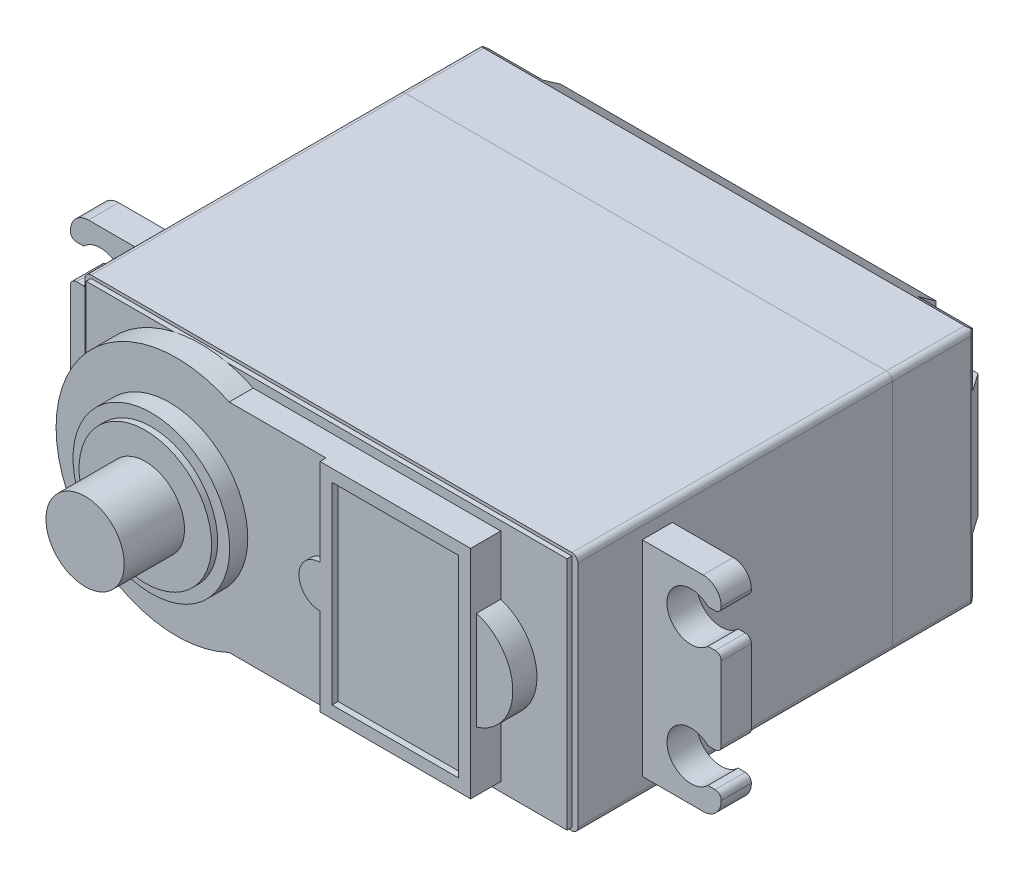
SolidWorks part; units mm, degrees
ref_plane "Front Plane" through (0, 0, 0) normal (0, 0, 1) x (1, 0, 0)
ref_plane "Top Plane" through (0, 0, 0) normal (0, 1, 0) x (1, 0, 0)
ref_plane "Right Plane" through (0, 0, 0) normal (1, 0, 0) x (0, 0, -1)
sketch "Sketch1" plane through (0, 0, 0) normal (0, 0, 1) x (1, 0, 0)
  line L1 (-20.45, 10) -> (20.45, 10)
  line L2 (-20.45, 10) -> (-20.45, -10)
  line L3 (-20.45, -10) -> (20.45, -10)
  line L4 (20.45, 10) -> (20.45, -10)
  line L5 (-20.45, 10) -> (20.45, -10) construction
  line L6 (-20.45, -10) -> (20.45, 10) construction
  point P0 (0, 0)
  dimension "D1" = 40.9
  dimension "D2" = 20
extrude "Boss-Extrude1" add sketch "Sketch1" along normal blind 19.3
sketch "Sketch2" plane through (0, 0, 19.3) normal (0, 0, 1) x (1, 0, 0)
  line L4 (20.45, -10) -> (20.45, 10)
  line L5 (20.45, 10) -> (-20.45, 10)
  line L6 (-20.45, 10) -> (-20.45, -10)
  line L7 (-20.45, -10) -> (20.45, -10)
  line L8 (20.45, -10) -> (20.45, 10)
  line L9 (20.45, 10) -> (-20.45, 10)
  line L10 (-20.45, 10) -> (-20.45, -10)
  line L11 (-20.45, -10) -> (20.45, -10)
  dimension "D1" = 0
extrude "Boss-Extrude2" add sketch "Sketch2" along normal blind 6.8 separate body
sketch "Sketch3" plane through (0, 0, 0) normal (0, 0, -1) x (-1, 0, 0)
  line L4 (-20.45, 10) -> (-20.45, -10)
  line L5 (-20.45, -10) -> (20.45, -10)
  line L6 (20.45, -10) -> (20.45, 10)
  line L7 (20.45, 10) -> (-20.45, 10)
  line L8 (-20.45, 10) -> (-20.45, -10)
  line L9 (-20.45, -10) -> (20.45, -10)
  line L10 (20.45, -10) -> (20.45, 10)
  line L11 (20.45, 10) -> (-20.45, 10)
  dimension "D1" = 0
extrude "Boss-Extrude3" add sketch "Sketch3" along normal blind 8.5 separate body
chamfer "Chamfer1" distance 2 angle 35 4 edges at (-20.45, 0, -8.5) (0, -10, -8.5) (20.45, 0, -8.5) (0, 10, -8.5)
sketch "Sketch4" plane through (0, 0, -8.5) normal (0, 0, -1) x (-1, 0, 0)
  line L0 (0, 8.5996) -> (0, -8.5996) construction
  line L1 (-20.45, 10) -> (-15.57, 10)
  line L2 (-20.45, 10) -> (-20.45, 5.12)
  line L3 (-20.45, 5.12) -> (-17.57, 5.12)
  line L4 (-15.57, 10) -> (-15.57, 7.12)
  line L5 (19.0496, 8.5996) -> (-19.0496, 8.5996) construction
  line L6 (-19.0496, -8.5996) -> (19.0496, -8.5996) construction
  line L7 (0, 0) -> (19.0496, 0) construction
  line L8 (19.0496, -8.5996) -> (19.0496, 8.5996) construction
  line L9 (20.45, 5.12) -> (17.57, 5.12)
  line L10 (20.45, 10) -> (20.45, 5.12)
  line L11 (20.45, 10) -> (15.57, 10)
  line L12 (15.57, 10) -> (15.57, 7.12)
  line L13 (15.57, -10) -> (15.57, -7.12)
  line L14 (20.45, -10) -> (15.57, -10)
  line L15 (20.45, -10) -> (20.45, -5.12)
  line L16 (20.45, -5.12) -> (17.57, -5.12)
  line L17 (-15.57, -10) -> (-15.57, -7.12)
  line L18 (-20.45, -5.12) -> (-17.57, -5.12)
  line L19 (-20.45, -10) -> (-20.45, -5.12)
  line L20 (-20.45, -10) -> (-15.57, -10)
  arc A0 (-17.57, 5.12) -> (-15.57, 7.12) centre (-17.57, 7.12) ccw
  arc A1 (17.57, 5.12) -> (15.57, 7.12) centre (17.57, 7.12) cw
  arc A2 (17.57, -5.12) -> (15.57, -7.12) centre (17.57, -7.12) ccw
  arc A3 (-17.57, -5.12) -> (-15.57, -7.12) centre (-17.57, -7.12) cw
  dimension "D3" = 2
  dimension "D1" = 4.88
  dimension "D2" = 4.88
extrude "Cut-Extrude1" cut sketch "Sketch4" against normal blind 1.5
sketch "Sketch5" plane through (0, 0, 26.1) normal (0, 0, 1) x (1, 0, 0)
  line L0 (20.45, 10) -> (-20.45, 10) construction
  line L1 (-19.95, 9.75) -> (19.95, 9.75)
  line L2 (-19.95, 9.75) -> (-19.95, -9.75)
  line L3 (-19.95, -9.75) -> (19.95, -9.75)
  line L4 (19.95, 9.75) -> (19.95, -9.75)
  line L5 (-19.95, 9.75) -> (19.95, -9.75) construction
  line L6 (-19.95, -9.75) -> (19.95, 9.75) construction
  line L7 (-20.45, 10) -> (-20.45, -10) construction
  point P0 (0, 0)
  dimension "D1" = 0.25
  dimension "D2" = 0.5
extrude "Boss-Extrude4" add sketch "Sketch5" along normal blind 0.4
sketch "Sketch6" plane through (0, 0, 26.5) normal (0, 0, 1) x (1, 0, 0)
  line L0 (-19.95, 0) -> (19.95, 0) construction
  line L1 (-19.95, 9.75) -> (-19.95, -9.75) construction
  line L2 (19.95, -9.75) -> (19.95, 9.75) construction
  line L3 (-20.45, 10) -> (-20.45, -10) construction
  line L4 (20.45, 10) -> (-20.45, 10) construction
  line L5 (-6.09, 10) -> (-6.09, -10) construction
  line L6 (-20.45, -10) -> (20.45, -10) construction
  line L7 (-6.09, 8.9995) -> (14.45, 8.9995)
  line L8 (14.45, 8.9995) -> (14.45, 4.0952)
  line L9 (20.45, -10) -> (20.45, 10) construction
  line L10 (14.45, -8.9995) -> (14.45, -4.0952)
  line L11 (-6.09, -8.9995) -> (14.45, -8.9995)
  arc A0 (-6.09, 8.9995) -> (-6.09, -8.9995) centre (-10.45, 0) ccw
  arc A1 (14.45, -4.0952) -> (14.45, 4.0952) centre (13.1549, 0) ccw
  point P24 (17.45, 0)
  dimension "D1" = 14.36
  dimension "D2" = 3
  dimension "D3" = 6
extrude "Boss-Extrude5" add sketch "Sketch6" along normal blind 2
sketch "Sketch7" plane through (0, 0, 28.5) normal (0, 0, 1) x (1, 0, 0)
  circle A0 centre (-11.0436, 0) radius 6.5
  dimension "D1" = 13
extrude "Boss-Extrude6" add sketch "Sketch7" along normal blind 1.5
sketch "Sketch8" plane through (0, 0, 30) normal (0, 0, 1) x (1, 0, 0)
  circle A0 centre (-11.0436, 0) radius 5.5
  dimension "D1" = 11
extrude "Boss-Extrude7" add sketch "Sketch8" along normal blind 0.5
sketch "Sketch9" plane through (0, 0, 30.5) normal (0, 0, 1) x (1, 0, 0)
  circle A0 centre (-11.0436, 0) radius 3.25
  dimension "D1" = 6.5
extrude "Boss-Extrude8" add sketch "Sketch9" along normal blind 5
sketch "Sketch10" plane through (0, 0, 28.5) normal (0, 0, 1) x (1, 0, 0)
  line L0 (14.45, 8.9995) -> (-6.09, 8.9995) construction
  line L1 (1.95, 8.9995) -> (14.45, 8.9995)
  line L2 (1.95, 8.9995) -> (1.95, 1.75)
  line L3 (1.95, -8.9995) -> (14.45, -8.9995)
  line L4 (14.45, 8.9995) -> (14.45, -8.9995)
  line L5 (2.95, 7.9995) -> (13.45, 7.9995)
  line L6 (13.45, 7.9995) -> (13.45, -7.9995)
  line L7 (2.95, -7.9995) -> (13.45, -7.9995)
  line L8 (2.95, 7.9995) -> (2.95, -7.9995)
  line L9 (1.95, -1.75) -> (1.95, -8.9995)
  line L10 (1.95, 8.9995) -> (1.95, -8.9995) construction
  arc A0 (1.95, 1.75) -> (1.95, -1.75) centre (1.95, 0) ccw
  dimension "D1" = 12.5
  dimension "D2" = 1
extrude "Boss-Extrude9" add sketch "Sketch10" along normal blind 0.5
fillet "Fillet1" radius 0.5 4 edges at (-20.45, -10, 9.65) (20.45, -10, 9.65) (20.45, 10, 9.65) (-20.45, 10, 9.65)
fillet "Fillet2" radius 0.5 4 edges at (-20.45, 10, 22.7) (20.45, 10, 22.7) (20.45, -10, 22.7) (-20.45, -10, 22.7)
fillet "Fillet4" radius 0.5 4 edges at (-20.45, 10, -3.25) (20.45, 10, -3.25) (20.45, -10, -3.25) (-20.45, -10, -3.25)
sketch "Sketch11" plane through (0, 0, 26.5) normal (0, 0, 1) x (1, 0, 0)
  line L0 (0.2, 0) -> (27, 0) construction
  line L1 (20.45, 8.5) -> (25.5, 8.5)
  line L2 (20.45, -9.5) -> (20.45, 9.5) construction
  line L3 (27, 7) -> (27, 6.9283)
  line L4 (0, 10) -> (0, -10) construction
  line L5 (19.95, 10) -> (-19.95, 10) construction
  line L6 (-19.95, -10) -> (19.95, -10) construction
  line L7 (25.9, 8.5) -> (25.9, -8.5) construction
  line L8 (25.9, 6.4283) -> (26.5, 6.4283)
  line L9 (25.9, 3.5717) -> (26.5, 3.5717)
  line L10 (27, 3.0717) -> (27, -3.0717)
  line L11 (25.9, -3.5717) -> (26.5, -3.5717)
  line L12 (25.9, -6.4283) -> (26.5, -6.4283)
  line L13 (27, -7) -> (27, -6.9283)
  line L14 (20.45, -8.5) -> (25.5, -8.5)
  line L15 (20.45, 8.5) -> (20.45, -8.5)
  arc A0 (1.95, 1.75) -> (1.95, -1.75) centre (1.95, 0) ccw construction
  arc A1 (20.45, 9.5) -> (19.95, 10) centre (19.95, 9.5) ccw construction
  arc A2 (25.9, 6.4283) -> (25.9, 3.5717) centre (24.5, 5) ccw
  arc A3 (26.5, 3.5717) -> (27, 3.0717) centre (26.5, 3.0717) cw
  arc A4 (26.5, 6.4283) -> (27, 6.9283) centre (26.5, 6.9283) ccw
  arc A5 (25.5, 8.5) -> (27, 7) centre (25.5, 7) cw
  arc A6 (25.5, -8.5) -> (27, -7) centre (25.5, -7) ccw
  arc A7 (26.5, -6.4283) -> (27, -6.9283) centre (26.5, -6.9283) cw
  arc A8 (26.5, -3.5717) -> (27, -3.0717) centre (26.5, -3.0717) ccw
  arc A9 (25.9, -6.4283) -> (25.9, -3.5717) centre (24.5, -5) cw
  point P30 (27, 3.5717)
  point P35 (27, 8.5)
  point P37 (25.9, 0)
  point P50 (27, -8.5)
  point P51 (27, -3.5717)
  dimension "D2" = 1
  dimension "D3" = 4
  dimension "D7" = 0.5
  dimension "D8" = 1.5
  dimension "D1" = 6.55
  dimension "D4" = 5
  dimension "D5" = 24.3
  dimension "D6" = 1.1
extrude "Boss-Extrude10" add sketch "Sketch11" against normal blind 2.5 from offset 5.74 offset against normal yes
mirror "Mirror1" about plane through (0, 0, 0) normal (1, 0, 0) of "Boss-Extrude10"
